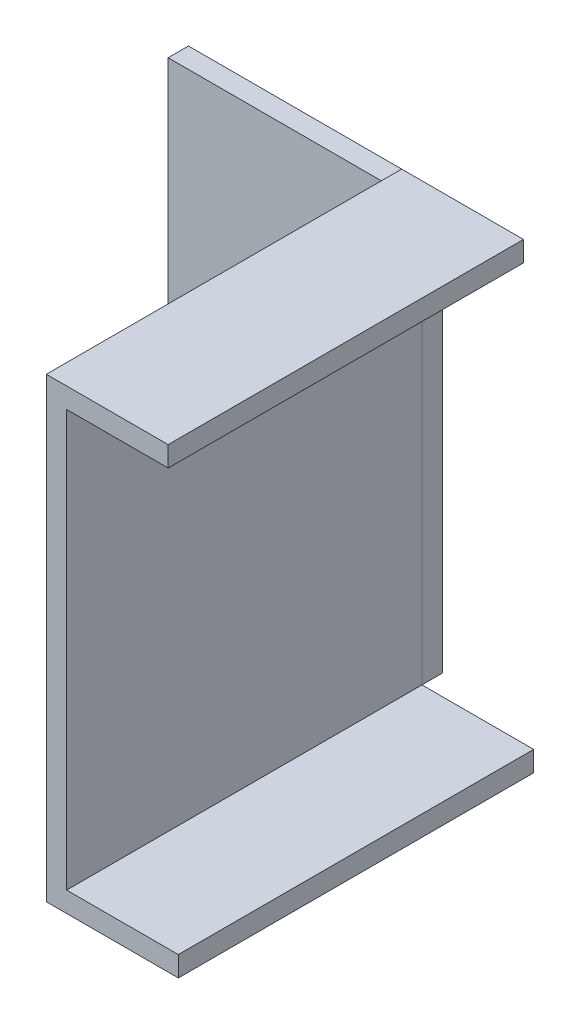
SolidWorks part; units mm, degrees
material "AISI 304"
ref_plane "前视基准面" through (0, 0, 0) normal (0, 0, 1) x (1, 0, 0)
ref_plane "上视基准面" through (0, 0, 0) normal (0, 1, 0) x (1, 0, 0)
ref_plane "右视基准面" through (0, 0, 0) normal (1, 0, 0) x (0, 0, -1)
sketch "Sketch1" plane through (0, 0, 0) normal (0, 0, 1) x (1, 0, 0)
  line L0 (0, 0) -> (0, 45)
  line L1 (0, 45) -> (12, 45)
  line L2 (12, 45) -> (12, 43)
  line L3 (12, 43) -> (2, 43)
  line L4 (2, 43) -> (2, 2)
  line L5 (2, 2) -> (13, 2)
  line L6 (13, 2) -> (13, 0)
  line L7 (13, 0) -> (0, 0)
  point P6 (13, 1)
  dimension "D1" = 45
  dimension "D2" = 2
  dimension "D3" = 2
  dimension "D4" = 2
  dimension "D5" = 12
  dimension "D6" = 13
extrude "Boss-Extrude1" add sketch "Sketch1" along normal blind 35
sketch "Sketch2" plane through (0, 0, 0) normal (0, 0, -1) x (-1, 0, 0)
  line L7 (0, 0) -> (-13, 0) construction
  line L8 (-2, 43) -> (23, 43)
  line L9 (-2, 43) -> (-2, 2)
  line L10 (-2, 2) -> (23, 2)
  line L11 (23, 43) -> (23, 2)
  dimension "D1" = 2
  dimension "D2" = 25
extrude "Boss-Extrude2" add sketch "Sketch2" along normal blind 2 separate body
